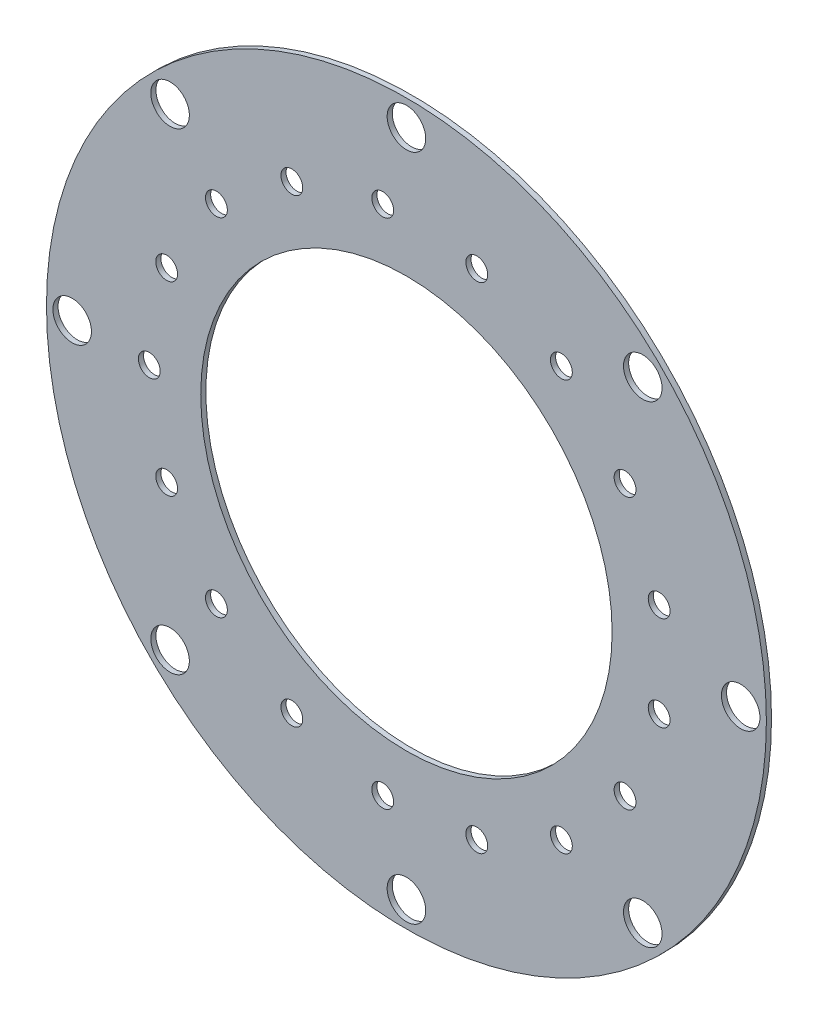
SolidWorks part; units mm, degrees
ref_plane "Front Plane" through (0, 0, 0) normal (0, 0, 1) x (1, 0, 0)
ref_plane "Top Plane" through (0, 0, 0) normal (0, 1, 0) x (1, 0, 0)
ref_plane "Right Plane" through (0, 0, 0) normal (1, 0, 0) x (0, 0, -1)
sketch "Sketch1" plane through (0, 0, 0) normal (0, 0, 1) x (1, 0, 0)
  circle A0 centre (0, 0) radius 70
  dimension "D1" = 140
extrude "Cap" add sketch "Sketch1" along normal mid plane 19 contours A0
sketch "Sketch2" plane through (0, 0, 9.5) normal (0, 0, 1) x (1, 0, 0)
  circle A0 centre (0, 0) radius 50 construction
  circle A1 centre (-50, 0) radius 2.125
  dimension "D1" = 100
  dimension "D2" = 4.25
extrude "Dowel Holes" cut sketch "Sketch2" against normal through all contours A1
pattern_circular "CirPattern1" count 17 over 360 about axis through (0, 0, 0) along (0, 0, 1) of "Dowel Holes"
sketch "Sketch3" plane through (0, 0, 9.5) normal (0, 0, 1) x (1, 0, 0)
  circle A0 centre (0, 0) radius 31.05
  dimension "D1" = 62.1
extrude "Center Hole" cut sketch "Sketch3" against normal blind 15
sketch "Sketch7" plane through (0, 0, -5.5) normal (0, 0, 1) x (1, 0, 0)
  circle A0 centre (0, 0) radius 40
  dimension "D1" = 80
extrude "OutputShaft Hole" cut sketch "Sketch7" against normal through all
hole_wizard "CBORE for M4 Hex Head Machine Screw3" positions "Sketch5" profile "Sketch6" counterbore size "M4" standard "ANSI Metric"
sketch "Sketch5" plane through (0, 0, -9.5) normal (0, 0, -1) x (-1, 0, 0)
  circle A0 centre (0, 0) radius 65 construction
  point P4 (-65, 0)
  dimension "D1" = 130
sketch "Sketch6" plane through (65, 0, -9.5) normal (1, 0, 0) x (0, 1, 0)
  line L0 (0, 0) -> (0, 65)
  line L1 (0, 65) -> (1.95, 65)
  line L2 (1.95, 65) -> (1.95, 2.63)
  line L3 (1.95, 2.63) -> (3.75, 2.63)
  line L4 (3.75, 2.63) -> (3.75, 0)
  line L5 (3.75, 0) -> (0, 0)
  line L10 (0, 65) -> (-1.95, 65) construction
  line L11 (0, -6.35) -> (0, 107.95) construction
  dimension "Hole Dia." = 3.9
  dimension "Hole Depth" = 65
  dimension "C'Bore Dia." = 7.5
  dimension "C'Bore Depth" = 2.63
  dimension "Drill Angle" = 180
pattern_circular "CirPattern2" count 8 over 360 about axis through (0, 0, 0) along (0, 0, 1) of "CBORE for M4 Hex Head Machine Screw3"
sketch "Sketch8" plane through (0, 0, 9.5) normal (0, 0, 1) x (1, 0, 0)
  circle A0 centre (0, 0) radius 37.75
  dimension "D1" = 75.5
extrude "Cut-Extrude4" cut sketch "Sketch8" against normal blind 2
sketch "Sketch9" plane through (0, 0, 0) normal (0, 1, 0) x (1, 0, 0)
  line L1 (-78.4737, -9.6627) -> (79.1759, -9.6627)
  line L2 (-78.4737, -9.6627) -> (-78.4737, 8.5)
  line L3 (-78.4737, 8.5) -> (79.1759, 8.5)
  line L4 (79.1759, -9.6627) -> (79.1759, 8.5)
  line L6 (-44.4986, 9.5) -> (-48.7486, 9.5) construction
  point P6 (-78.4737, -12.6627)
  dimension "D1" = 1
extrude "Allignment" cut sketch "Sketch9" against normal through all both and the other way through all
chamfer "Chamfer1" [suppressed] distance 1 angle 45
